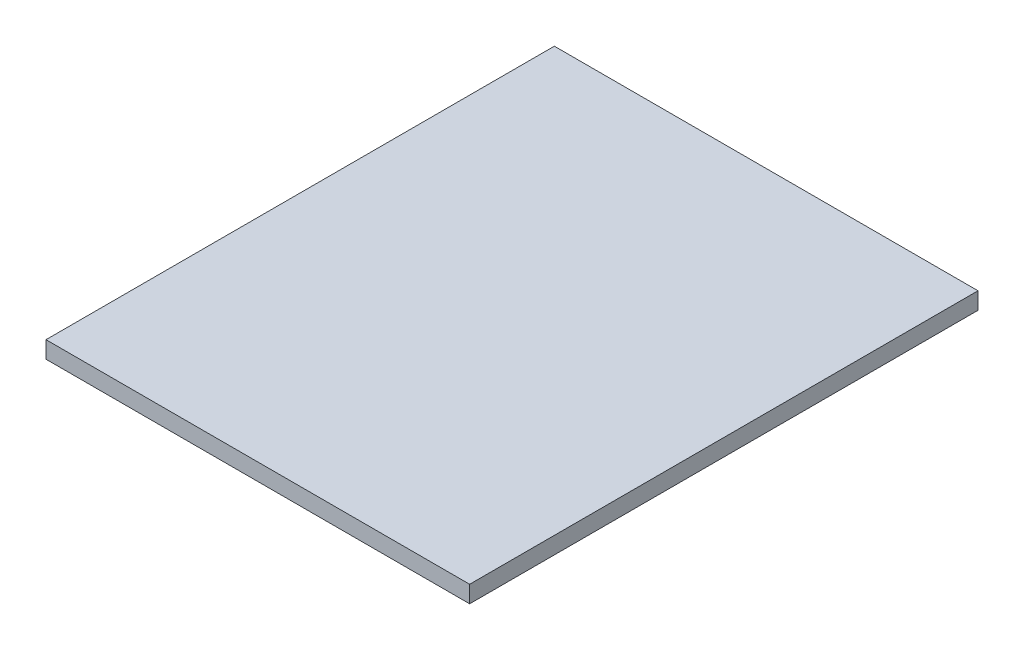
SolidWorks part; units mm, degrees
material "6061 Alloy"
ref_plane "Front Plane" through (0, 0, 0) normal (0, 0, 1) x (1, 0, 0)
ref_plane "Top Plane" through (0, 0, 0) normal (0, 1, 0) x (1, 0, 0)
ref_plane "Right Plane" through (0, 0, 0) normal (1, 0, 0) x (0, 0, -1)
sketch "Sketch1" plane through (0, 0, 0) normal (0, 1, 0) x (1, 0, 0)
  line L1 (-125, -150) -> (125, -150)
  line L2 (-125, -150) -> (-125, 150)
  line L3 (-125, 150) -> (125, 150)
  line L4 (125, -150) -> (125, 150)
  line L5 (-125, -150) -> (125, 150) construction
  line L6 (-125, 150) -> (125, -150) construction
  point P0 (0, 0)
  dimension "D1" = 250
  dimension "D2" = 300
extrude "Boss-Extrude1" add sketch "Sketch1" along normal blind 10
